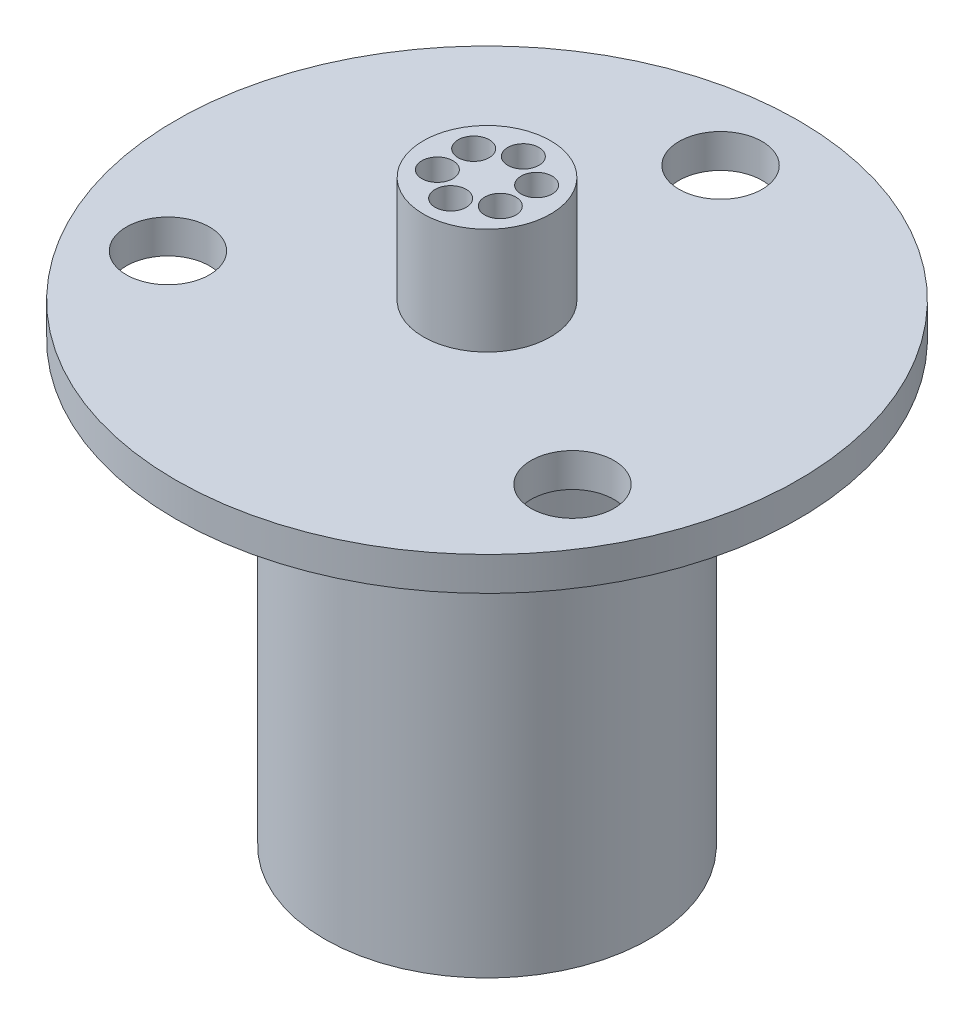
SolidWorks part; units mm, degrees
ref_plane "Plano frontal" through (0, 0, 0) normal (0, 0, 1) x (1, 0, 0)
ref_plane "Plano superior" through (0, 0, 0) normal (0, 1, 0) x (1, 0, 0)
ref_plane "Plano direito" through (0, 0, 0) normal (1, 0, 0) x (0, 0, -1)
sketch "Esboço1" plane through (0, 0, 0) normal (0, 1, 0) x (1, 0, 0)
  circle A0 centre (0, 0) radius 6.25
  dimension "D1" = 12.5
extrude "Ressalto-extrusão1" add sketch "Esboço1" along normal blind 16.9
sketch "Esboço2" plane through (0, 16.9, 0) normal (0, 1, 0) x (1, 0, 0)
  circle A0 centre (0, 0) radius 12
  dimension "D1" = 24
extrude "Ressalto-extrusão2" add sketch "Esboço2" along normal blind 1.3
sketch "Esboço3" plane through (0, 18.2, 0) normal (0, 1, 0) x (1, 0, 0)
  circle A0 centre (0, 9) radius 1.6
  circle A1 centre (7.7942, -4.5) radius 1.6
  circle A2 centre (-7.7942, -4.5) radius 1.6
  point P10 (0, 0)
  dimension "D1" = 3.2
  dimension "D2" = 9
  dimension "D3" = 3
extrude "Corte-extrusão1" cut sketch "Esboço3" against normal through all
sketch "Esboço4" plane through (0, 18.2, 0) normal (0, 1, 0) x (1, 0, 0)
  circle A0 centre (0, 0) radius 2.45
  dimension "D1" = 4.9
extrude "Ressalto-extrusão3" add sketch "Esboço4" along normal blind 4.1
sketch "Esboço5" plane through (0, 22.3, 0) normal (0, 1, 0) x (1, 0, 0)
  circle A0 centre (0, 1.4) radius 0.6
  circle A1 centre (1.2124, 0.7) radius 0.6
  circle A2 centre (1.2124, -0.7) radius 0.6
  circle A3 centre (0, -1.4) radius 0.6
  circle A4 centre (-1.2124, -0.7) radius 0.6
  circle A5 centre (-1.2124, 0.7) radius 0.6
  point P16 (0, 0)
  dimension "D1" = 1.2
  dimension "D2" = 1.4
  dimension "D3" = 6
extrude "Corte-extrusão2" cut sketch "Esboço5" against normal blind 1
sketch "Esboço7" plane through (0, 0, 0) normal (0, -1, 0) x (1, 0, 0)
  line L0 (0, 6.25) -> (0, -6.25) construction
  line L1 (-6.25, 0) -> (6.25, 0) construction
  circle A0 centre (0, 4.5) radius 0.6
  circle A1 centre (1.9018, 4.0784) radius 0.6
  circle A2 centre (0, 0) radius 6.25 construction
  circle A3 centre (0, 0) radius 6.25 construction
  circle A4 centre (-1.9018, 4.0784) radius 0.6
  circle A5 centre (-1.9018, -4.0784) radius 0.6
  circle A6 centre (1.9018, -4.0784) radius 0.6
  circle A7 centre (0, -4.5) radius 0.6
  point P8 (0, 0)
  dimension "D1" = 4.5
  dimension "D2" = 1.2
  dimension "D3" = 2
extrude "Corte-extrusão3" cut sketch "Esboço7" against normal blind 1
